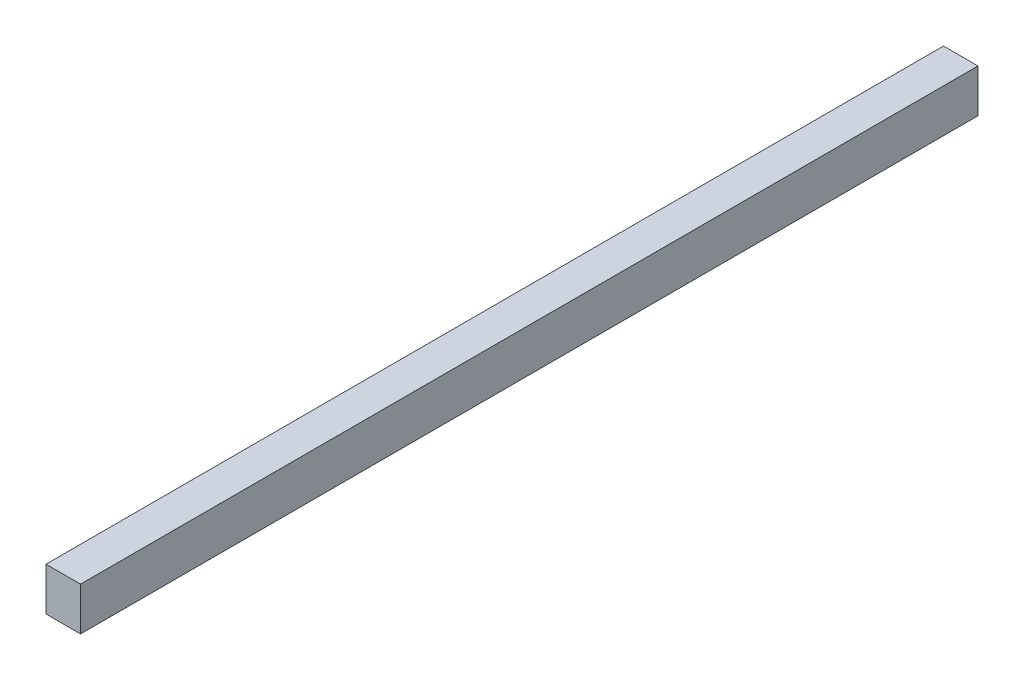
SolidWorks part; units mm, degrees
ref_plane "前视基准面" through (0, 0, 0) normal (0, 0, 1) x (1, 0, 0)
ref_plane "上视基准面" through (0, 0, 0) normal (0, 1, 0) x (1, 0, 0)
ref_plane "右视基准面" through (0, 0, 0) normal (1, 0, 0) x (0, 0, -1)
sketch "草图1" plane through (0, 0, 0) normal (0, 0, 1) x (1, 0, 0)
  line L0 (0, -55) -> (0, 55) construction
  line L1 (0, 0) -> (4, 0)
  line L2 (0, 0) -> (0, 5)
  line L3 (0, 5) -> (4, 5)
  line L4 (4, 0) -> (4, 5)
  point P6 (0, 0)
extrude "凸台-拉伸1" add sketch "草图1" along normal mid plane 104
